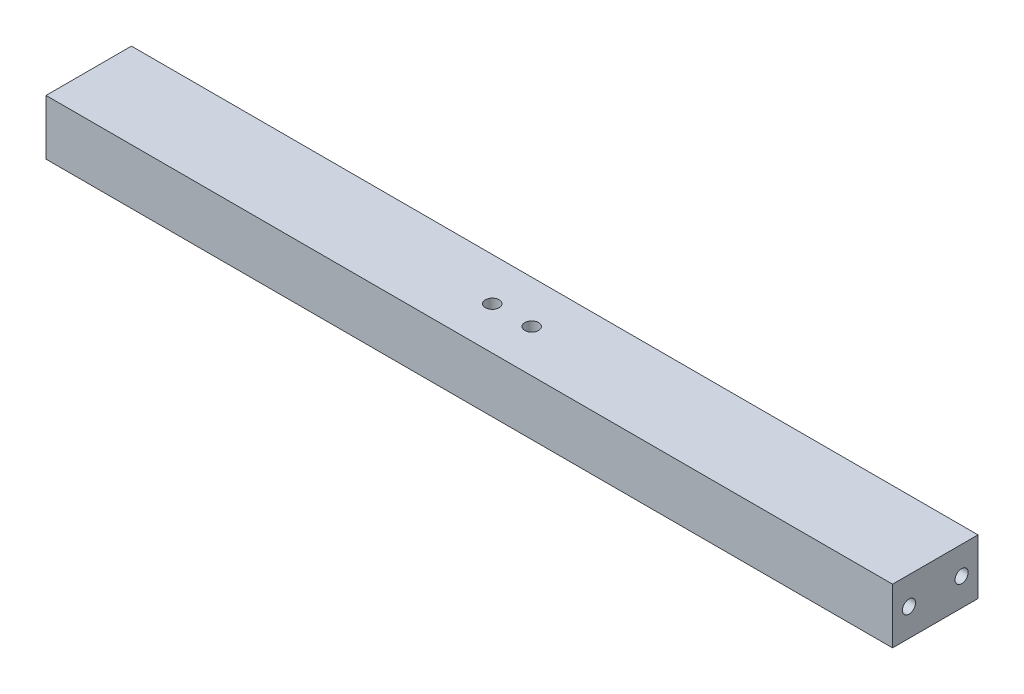
SolidWorks part; units mm, degrees
ref_plane "Piano frontale" through (0, 0, 0) normal (0, 0, 1) x (1, 0, 0)
ref_plane "Piano superiore" through (0, 0, 0) normal (0, 1, 0) x (1, 0, 0)
ref_plane "Piano destro" through (0, 0, 0) normal (1, 0, 0) x (0, 0, -1)
sketch "Schizzo1" plane through (0, 0, 0) normal (0, 0, 1) x (1, 0, 0)
  line L0 (-461.9166, 0) -> (446.0267, 0) construction
  line L1 (-322, 21) -> (322, 21)
  line L2 (-322, -21) -> (322, -21)
  line L3 (-322, 21) -> (-322, -21)
  line L4 (322, 21) -> (322, -21)
  dimension "D1" = 42
  dimension "D2" = 322
  dimension "D3" = 322
extrude "Estrusione-Estrusione1" add sketch "Schizzo1" against normal blind 65
sketch "Schizzo2" plane through (0, -21, 0) normal (0, -1, 0) x (1, 0, 0)
  line L0 (-312, -60) -> (-312, -5)
  line L2 (-312, -5) -> (312, -5)
  line L3 (312, -5) -> (312, -60)
  line L4 (-322, -65) -> (-322, 0) construction
  line L5 (322, -65) -> (322, 0) construction
  line L6 (-322, 0) -> (322, 0) construction
  line L7 (-312, -60) -> (312, -60)
  line L8 (-322, -65) -> (322, -65) construction
  dimension "D1" = 10
  dimension "D2" = 10
  dimension "D3" = 5
  dimension "D4" = 5
extrude "Taglio-Estrusione1" cut sketch "Schizzo2" against normal offset from surface (32 mm away) 10 up to face at (0, 21, -32.5)
sketch "Schizzo4" plane through (0, 21, -21) normal (0, -1, 0) x (1, 0, 0)
  line L0 (0, 78.385) -> (0, -97.8942) construction
  line L1 (-345.9389, 21) -> (355.6217, 21) construction
  line L3 (322, -44) -> (-322, -44) construction
  circle A0 centre (-15, -11.5) radius 5.25
  circle A1 centre (15, -11.5) radius 5.25
  dimension "D1" = 10.5
  dimension "D2" = 10.5
  dimension "D3" = 15
  dimension "D4" = 15
  dimension "D5" = 32.5
  dimension "D6" = 32.5
extrude "Taglio-Estrusione2" cut sketch "Schizzo4" along normal up to surface (10 mm away) up to face at (0, 11, -32.5)
sketch "Schizzo5" plane through (322, 0, 0) normal (1, 0, 0) x (0, 0, -1)
  line L0 (-3.8227, 0) -> (72.9719, 0) construction
  line L1 (34.5746, 23.9456) -> (34.5746, -26.4773) construction
  line L2 (65, -21) -> (65, 21) construction
  line L3 (0, -21) -> (0, 21) construction
  circle A0 centre (12.5, 0) radius 5
  circle A1 centre (52.5, 0) radius 5
  dimension "D1" = 10
  dimension "D2" = 10
  dimension "D3" = 12.5
  dimension "D4" = 12.5
extrude "Taglio-Estrusione3" cut sketch "Schizzo5" against normal up to surface (644 mm away) up to face at (-322, 0, -32.5)
